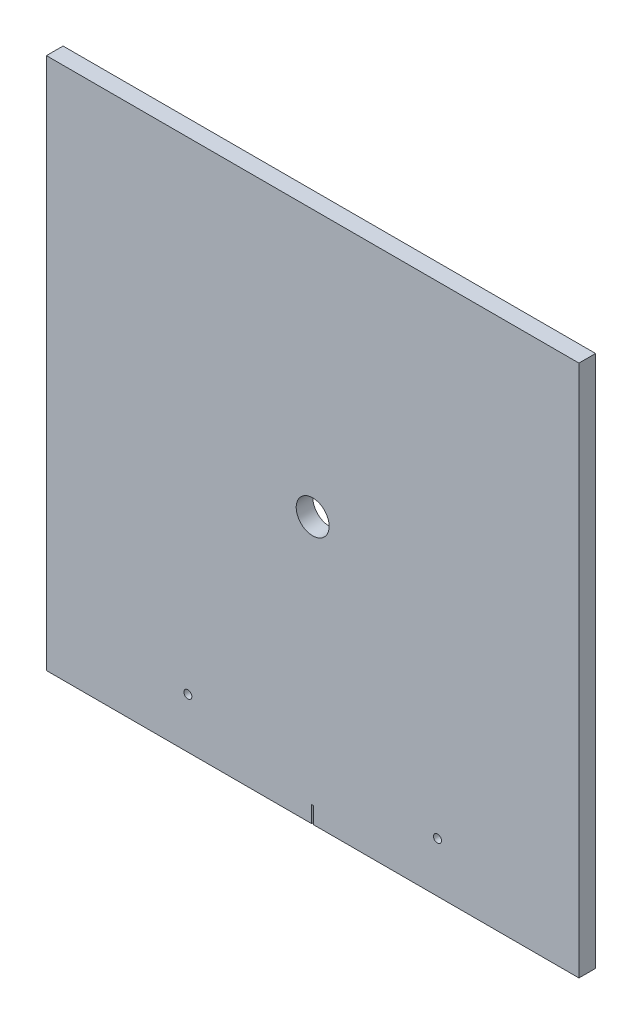
SolidWorks part; units mm, degrees
ref_plane "Front Plane" through (0, 0, 0) normal (0, 0, 1) x (1, 0, 0)
ref_plane "Top Plane" through (0, 0, 0) normal (0, 1, 0) x (1, 0, 0)
ref_plane "Right Plane" through (0, 0, 0) normal (1, 0, 0) x (0, 0, -1)
sketch "Sketch1" plane through (0, 0, 0) normal (0, 0, 1) x (1, 0, 0)
  line L0 (-101.6, 101.6) -> (101.6, -101.6) construction
  line L1 (-101.6, 101.6) -> (101.6, 101.6)
  line L2 (-101.6, 101.6) -> (-101.6, -101.6)
  line L3 (-101.6, -101.6) -> (101.6, -101.6)
  line L4 (101.6, 101.6) -> (101.6, -101.6)
  line L5 (101.6, -101.6) -> (100.9091, -101.3697) construction
  dimension "D1" = 203.2
  dimension "D2" = 203.2
extrude "Extrude1" add sketch "Sketch1" along normal blind 6.35
sketch "Sketch2" plane through (0, 0, 6.35) normal (0, 0, 1) x (1, 0, 0)
  circle A0 centre (0, 0) radius 6.2865
  dimension "D1" = 12.573
extrude "Extrude2" cut sketch "Sketch2" against normal through all
sketch "Sketch3" plane through (0, 0, 6.35) normal (0, 0, 1) x (1, 0, 0)
  line L0 (-1000, 0) -> (49000, 0) construction
  line L1 (0, -1000) -> (0, 49000) construction
  line L2 (0, 0) -> (25000, -43301.2702) construction
  line L3 (0, 0) -> (-25000, -43301.2702) construction
  circle A0 centre (-47.625, -82.4889) radius 1.524
  circle A1 centre (47.625, -82.4889) radius 1.524
  dimension "D2" = 3.048
  dimension "D4" = 3.048
  dimension "D1" = 60
  dimension "D3" = 95.25
  dimension "D5" = 95.25
extrude "Extrude3" cut sketch "Sketch3" against normal through all
sketch "Sketch4" plane through (0, 0, 6.35) normal (0, 0, 1) x (1, 0, 0)
  line L0 (0, -1000) -> (0, 49000) construction
  line L1 (-0.3969, -961.5871) -> (-0.3969, 49038.4129) construction
  line L2 (0.3969, -960.1422) -> (0.3969, 49039.8578) construction
  line L3 (-0.3969, -95.25) -> (0.3969, -95.25)
  line L4 (-0.3969, -95.25) -> (-0.3969, -101.6)
  line L5 (-0.3969, -101.6) -> (0.3969, -101.6)
  line L6 (0.3969, -101.6) -> (0.3969, -95.25)
  dimension "D1" = 0.3969
  dimension "D2" = 0.3969
  dimension "D3" = 95.25
  dimension "D4" = 101.6
extrude "Extrude4" cut sketch "Sketch4" against normal blind 6.35
